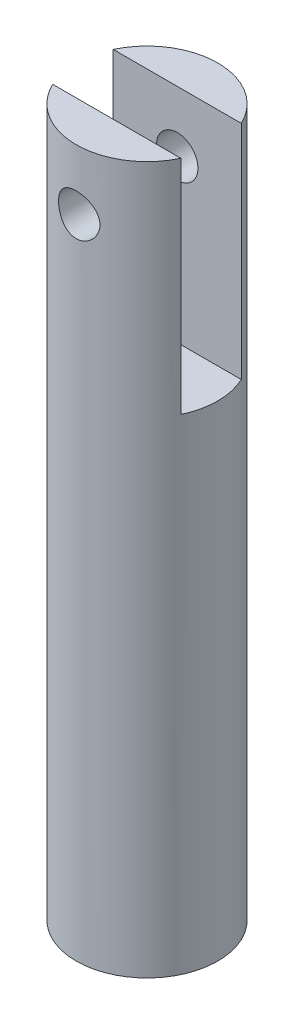
SolidWorks part; units mm, degrees
material "Alloy Steel"
ref_plane "Front Plane" through (0, 0, 0) normal (0, 0, 1) x (1, 0, 0)
ref_plane "Top Plane" through (0, 0, 0) normal (0, 1, 0) x (1, 0, 0)
ref_plane "Right Plane" through (0, 0, 0) normal (1, 0, 0) x (0, 0, -1)
sketch "Sketch1" plane through (0, 0, 0) normal (0, 1, 0) x (1, 0, 0)
  circle A0 centre (0, 0) radius 5.5626
  dimension "D1" = 11.1252
extrude "Boss-Extrude1" add sketch "Sketch1" along normal blind 55.5244
sketch "Sketch2" plane through (0, 0, 0) normal (0, 0, 1) x (1, 0, 0)
  line L0 (5.5626, 55.5244) -> (-5.5626, 55.5244) construction
  circle A0 centre (0, 50.7619) radius 1.6256
  dimension "D1" = 3.2512
  dimension "D2" = 4.7625
extrude "Cut-Extrude1" cut sketch "Sketch2" against normal through all both and the other way through all
sketch "Sketch3" plane through (0, 0, 0) normal (1, 0, 0) x (0, 0, -1)
  line L0 (5.5626, 55.5244) -> (-5.5626, 55.5244) construction
  line L1 (2.3749, 38.1) -> (-2.3749, 38.1)
  line L2 (2.3749, 38.1) -> (2.3749, 55.5244)
  line L3 (2.3749, 55.5244) -> (-2.3749, 55.5244)
  line L4 (-2.3749, 38.1) -> (-2.3749, 55.5244)
  line L5 (2.3749, 38.1) -> (-2.3749, 55.5244) construction
  line L6 (2.3749, 55.5244) -> (-2.3749, 38.1) construction
  point P0 (0, 46.8122)
  dimension "D1" = 4.7498
  dimension "D2" = 17.4244
extrude "Cut-Extrude2" cut sketch "Sketch3" against normal through all both and the other way through all
